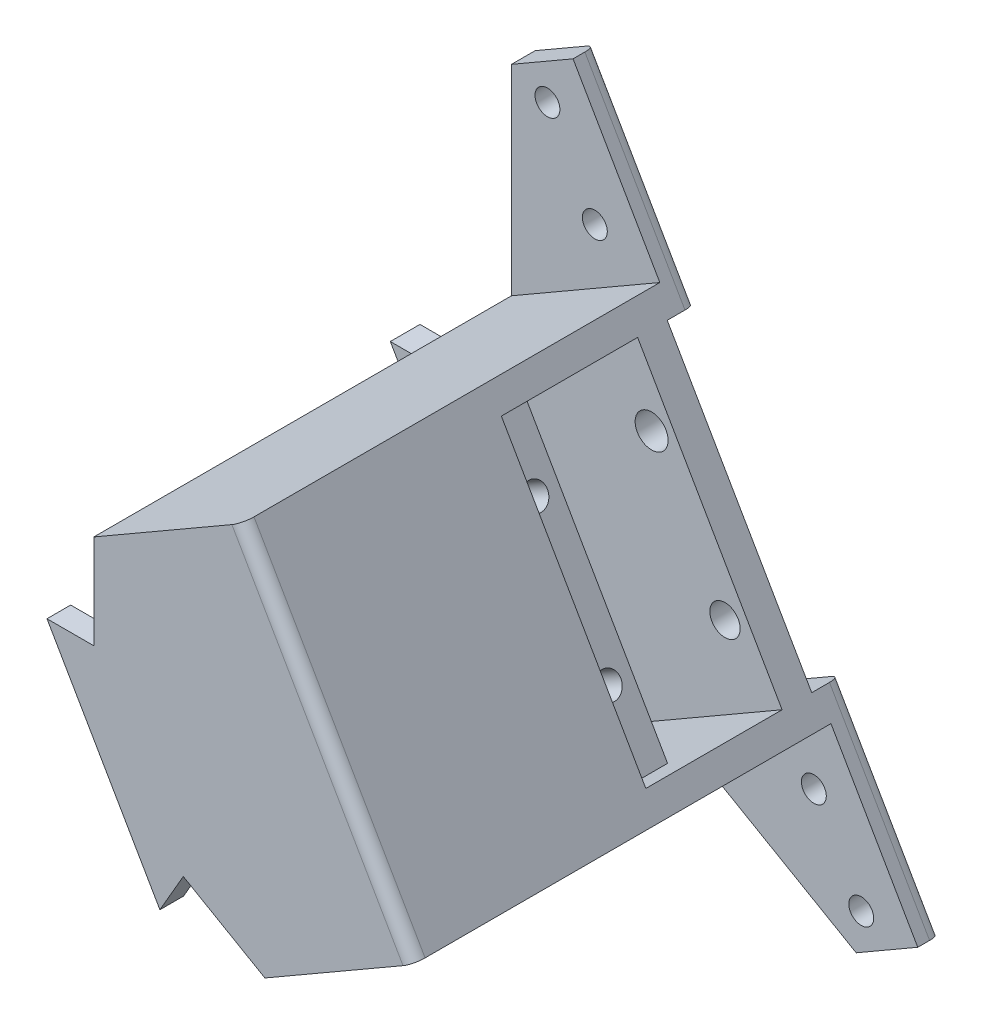
SolidWorks part; units mm, degrees
material "ABS"
ref_plane "前基準面" through (0, 0, 0) normal (0, 0, 1) x (1, 0, 0)
ref_plane "上基準面" through (0, 0, 0) normal (0, 1, 0) x (1, 0, 0)
ref_plane "右基準面" through (0, 0, 0) normal (1, 0, 0) x (0, 0, -1)
sketch "草圖1" plane through (0, 0, 0) normal (0, 0, 1) x (1, 0, 0)
  line L0 (35.0077, 40.3722) -> (54.4568, 40.3722)
  line L1 (54.4568, 40.3722) -> (69.5658, 14.2027)
  line L2 (69.5658, 14.2027) -> (59.8412, -2.6407)
  line L3 (59.8412, -2.6407) -> (35.0077, 40.3722)
  line L4 (46.5547, 40.3722) -> (65.6147, 7.3593)
  circle A0 centre (46.7546, 30.026) radius 2.1
  circle A1 centre (56.7546, 12.7055) radius 2.1
  dimension "D1" = 4.2
  dimension "D2" = 4.2
  dimension "D4" = 5
  dimension "D5" = 5
  dimension "D6" = 20
  dimension "D7" = 15.3462
  dimension "D8" = 11.7469
  dimension "D3" = 360
  dimension "D9" = 10
  dimension "D10" = 60
  dimension "D11" = 60
extrude "填料-伸長1" add sketch "草圖1" along normal blind 5 contours L4 L0 L3 L2 A1 A0 | L0 L4 L2 L1
sketch "草圖2" plane through (0, 0, 5) normal (0, 0, 1) x (1, 0, 0)
  line L0 (54.4568, 40.3722) -> (69.5658, 14.2027)
  line L1 (69.5658, 14.2027) -> (65.6147, 7.3593)
  line L2 (69.5658, 14.2027) -> (59.8412, -2.6407) construction
  line L3 (65.6147, 7.3593) -> (46.5547, 40.3722)
  line L4 (35.0077, 40.3722) -> (54.4568, 40.3722) construction
  line L5 (46.5547, 40.3722) -> (54.4568, 40.3722)
  line L6 (59.8412, -2.6407) -> (35.0077, 40.3722) construction
  dimension "D1" = 10
extrude "填料-伸長2" add sketch "草圖2" along normal blind 5
sketch "草圖3" plane through (0, 0, 0) normal (0, 0, -1) x (-1, 0, 0)
  line L0 (-69.5658, 14.2027) -> (-112.6419, -10.6673)
  line L1 (-112.6419, -10.6673) -> (-123.0342, -4.6673)
  line L2 (-123.0342, -4.6673) -> (-64.8491, 96.1122)
  line L3 (-64.8491, 96.1122) -> (-54.4568, 90.1122)
  line L4 (-54.4568, 90.1122) -> (-54.4568, 40.3722)
  line L5 (-54.4568, 40.3722) -> (-69.5658, 14.2027)
  dimension "D1" = 150
  dimension "D2" = 150
  dimension "D3" = 90
  dimension "D4" = 49.74
  dimension "D5" = 49.74
  dimension "D6" = 12
extrude "填料-伸長3" add sketch "草圖3" against normal blind 10
sketch "草圖4" plane through (0, 0, 0) normal (0, 0, -1) x (-1, 0, 0)
  line L0 (-123.0342, -4.6673) -> (-112.6419, -10.6673) construction
  line L1 (-64.8491, 96.1122) -> (-123.0342, -4.6673) construction
  circle A1 centre (-113.496, -4.1466) radius 2.1
  circle A2 centre (-105.496, 9.7098) radius 2.1
  dimension "D1" = 5.22
  dimension "D2" = 8
  dimension "D3" = 4.2
  dimension "D4" = 2
extrude "除料-伸長1" cut sketch "草圖4" against normal blind 10
sketch "草圖5" plane through (0, 0, 0) normal (0, 0, -1) x (-1, 0, 0)
  line L0 (-54.4568, 90.1122) -> (-64.8491, 96.1122) construction
  line L1 (-64.8491, 96.1122) -> (-123.0342, -4.6673) construction
  circle A0 centre (-60.5309, 87.5915) radius 2.1
  circle A1 centre (-68.5309, 73.7351) radius 2.1
  dimension "D1" = 5.22
  dimension "D2" = 8
  dimension "D3" = 4.2
  dimension "D4" = 2
extrude "除料-伸長2" cut sketch "草圖5" against normal through all
sketch "草圖6" plane through (0, 0, 10) normal (0, 0, 1) x (1, 0, 0)
  line L0 (79.4991, 70.7377) -> (54.4568, 56.2795)
  line L1 (64.8491, 96.1122) -> (123.0342, -4.6673) construction
  line L2 (54.4568, 40.3722) -> (54.4568, 90.1122) construction
  line L3 (83.3419, 6.2491) -> (108.3842, 20.7073)
  line L4 (112.6419, -10.6673) -> (69.5658, 14.2027) construction
  line L5 (123.0342, -4.6673) -> (112.6419, -10.6673) construction
  line L6 (54.4568, 90.1122) -> (64.8491, 96.1122) construction
  line L7 (83.3419, 6.2491) -> (112.6419, -10.6673)
  line L8 (112.6419, -10.6673) -> (123.0342, -4.6673)
  line L9 (123.0342, -4.6673) -> (108.3842, 20.7073)
  line L10 (79.4991, 70.7377) -> (64.8491, 96.1122)
  line L11 (64.8491, 96.1122) -> (54.4568, 90.1122)
  line L12 (54.4568, 90.1122) -> (54.4568, 56.2795)
  dimension "D1" = 29.3
  dimension "D2" = 29.3
extrude "除料-伸長3" cut sketch "草圖6" against normal blind 6
sketch "草圖7" plane through (0, 0, 10) normal (0, 0, 1) x (1, 0, 0)
  line L0 (78.8419, 8.8472) -> (106.1342, 24.6044)
  line L1 (83.3419, 6.2491) -> (69.5658, 14.2027) construction
  line L2 (79.4991, 70.7377) -> (108.3842, 20.7073) construction
  line L3 (106.1342, 24.6044) -> (108.3842, 20.7073)
  line L4 (108.3842, 20.7073) -> (83.3419, 6.2491)
  line L5 (83.3419, 6.2491) -> (78.8419, 8.8472)
  line L6 (54.4568, 56.2795) -> (79.4991, 70.7377)
  line L7 (79.4991, 70.7377) -> (81.7491, 66.8405)
  line L8 (81.7491, 66.8405) -> (54.4568, 51.0833)
  line L9 (54.4568, 40.3722) -> (54.4568, 56.2795) construction
  line L10 (54.4568, 51.0833) -> (54.4568, 56.2795)
  dimension "D1" = 4.5
  dimension "D2" = 4.5
extrude "填料-伸長4" add sketch "草圖7" along normal blind 64.5
sketch "草圖8" plane through (0, 0, 74.5) normal (0, 0, 1) x (1, 0, 0)
  line L0 (79.4991, 70.7377) -> (108.3842, 20.7073)
  line L1 (108.3842, 20.7073) -> (83.3419, 6.2491)
  line L2 (83.3419, 6.2491) -> (69.5658, 14.2027)
  line L3 (69.5658, 14.2027) -> (65.6147, 7.3593)
  line L4 (65.6147, 7.3593) -> (46.5547, 40.3722)
  line L5 (46.5547, 40.3722) -> (54.4568, 40.3722)
  line L6 (54.4568, 40.3722) -> (54.4568, 56.2795)
  line L7 (54.4568, 56.2795) -> (79.4991, 70.7377)
extrude "填料-伸長5" add sketch "草圖8" against normal blind 4
sketch "草圖9" plane through (90.2546, 52.1085, 0) normal (0.866, 0.5, 0) x (0, 0, -1)
  line L0 (-4, 21.511) -> (-74.5, 21.511) construction
  line L1 (-74.5, -36.2591) -> (-25, -36.2591)
  line L2 (-74.5, -36.2591) -> (-74.5, 21.511)
  line L3 (-74.5, 21.511) -> (-25, 21.511)
  line L4 (-25, -36.2591) -> (-25, 21.511)
  line L5 (-10, 17.011) -> (-10, -31.7591) construction
  dimension "D1" = 15
extrude "填料-伸長6" add sketch "草圖9" against normal blind 10
sketch "草圖10" plane through (90.2546, 52.1085, 0) normal (0.866, 0.5, 0) x (0, 0, -1)
  line L0 (0, 17.011) -> (-5, 17.011)
  line L1 (0, 50.811) -> (0, -65.5591) construction
  line L2 (-5, 17.011) -> (-5, -31.7591)
  line L3 (-5, -31.7591) -> (0, -31.7591)
  line L4 (0, -31.7591) -> (0, 17.011)
  line L5 (-25, 17.011) -> (-10, 17.011) construction
  line L6 (-25, -31.7591) -> (-10, -31.7591) construction
  line L7 (-10, 17.011) -> (-10, -31.7591) construction
  dimension "D1" = 0
  dimension "D2" = 0
  dimension "D3" = 5
extrude "除料-伸長4" cut sketch "草圖10" against normal blind 10
sketch "草圖11" plane through (0, 0, 5) normal (0, 0, -1) x (-1, 0, 0)
  line L0 (-73.0889, 61.8405) -> (-81.7491, 66.8405) construction
  line L1 (-97.4739, 19.6044) -> (-106.1342, 24.6044) construction
  line L2 (-81.7491, 66.8405) -> (-106.1342, 24.6044) construction
  circle A0 centre (-96.4969, 32.8967) radius 2.563
  circle A1 centre (-84.1118, 54.3482) radius 2.7806
  dimension "D1" = 12
  dimension "D2" = 12
  dimension "D3" = 4.2
  dimension "D4" = 4.2
extrude "除料-伸長5" cut sketch "草圖11" against normal up to next
fillet "圓角1" radius 2 3 edges at (73.2991, 81.4764, 0) (114.5842, 9.9685, 0) (93.9416, 45.7225, 74.5)
sketch "草圖12" plane through (90.2546, 52.1085, 0) normal (0.866, 0.5, 0) x (0, 0, -1)
  line L0 (-25, -31.7591) -> (-25, 17.011) construction
  line L1 (-25, 17.011) -> (-10, 17.011) construction
  line L2 (-25, -31.7591) -> (-10, -31.7591) construction
  circle A0 centre (-29, -19.7591) radius 2.1
  circle A1 centre (-29, 5.011) radius 2.1
  dimension "D1" = 4.2
  dimension "D2" = 4
  dimension "D3" = 4
  dimension "D4" = 4.2
  dimension "D5" = 12
  dimension "D6" = 12
extrude "除料-伸長6" cut sketch "草圖12" against normal blind 10
sketch "草圖13" plane through (90.2546, 52.1085, 0) normal (0.866, 0.5, 0) x (0, 0, -1)
  line L0 (-25, -31.7591) -> (-25, 17.011)
  line L1 (-25, -31.7591) -> (-33, -31.7591)
  line L2 (-25, 17.011) -> (-33, 17.011)
  line L3 (-33, -31.7591) -> (-33, 17.011)
  dimension "D1" = 8
extrude "除料-伸長7" cut sketch "草圖13" against normal blind 5
